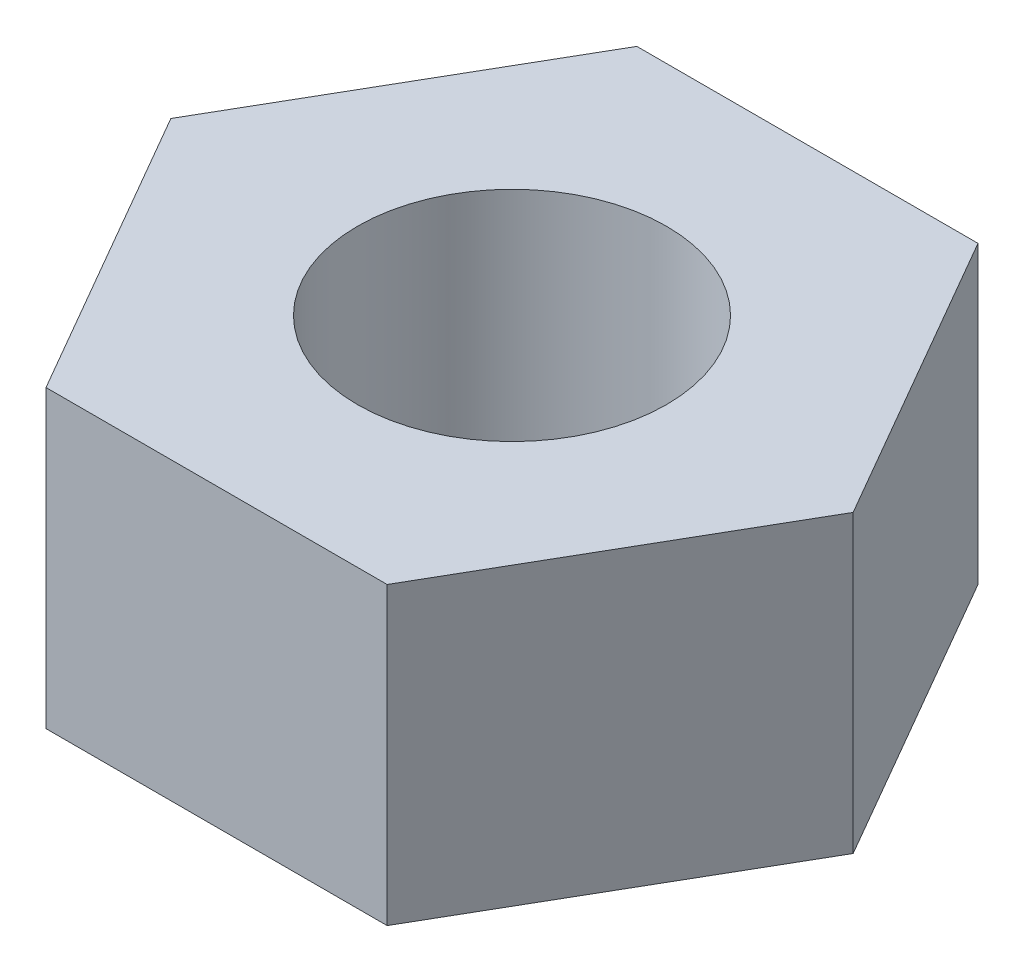
SolidWorks part; units mm, degrees
ref_plane "Front Plane" through (0, 0, 0) normal (0, 0, 1) x (1, 0, 0)
ref_plane "Top Plane" through (0, 0, 0) normal (0, 1, 0) x (1, 0, 0)
ref_plane "Right Plane" through (0, 0, 0) normal (1, 0, 0) x (0, 0, -1)
sketch "Sketch1" plane through (0, 0, 0) normal (0, 1, 0) x (1, 0, 0)
  line L0 (0, 0) -> (0, 6.5) construction
  line L1 (0, 0) -> (4.9464, 8.5675) construction
  line L3 (3.7528, 6.5) -> (-3.7528, 6.5)
  line L4 (-3.7528, 6.5) -> (-7.5056, 0)
  line L5 (-7.5056, 0) -> (-3.7528, -6.5)
  line L6 (-3.7528, -6.5) -> (3.7528, -6.5)
  line L7 (3.7528, -6.5) -> (7.5056, 0)
  line L8 (7.5056, 0) -> (3.7528, 6.5)
  circle A0 centre (0, 0) radius 6.5 construction
extrude "Boss-Extrude1" add sketch "Sketch1" along normal blind 6.5
hole_wizard "Tap Drill for M8x1.25 Tap1" positions "Sketch7" profile "Sketch8" hole size "M8x1.25" standard "BSI" end condition through all
sketch "Sketch7" plane through (0, 6.5, 0) normal (0, 1, 0) x (1, 0, 0)
  point P0 (0, 0)
sketch "Sketch8" plane through (0, 6.5, 0) normal (1, 0, 0) x (0, 0, 1)
  line L0 (0, 0) -> (0, 6.5)
  line L1 (0, 6.5) -> (3.4, 6.5)
  line L2 (3.4, 6.5) -> (3.4, 0)
  line L5 (3.4, 0) -> (0, 0)
  line L11 (0, -6.35) -> (0, 107.95) construction
  dimension "Thru Hole Dia." = 6.8
  dimension "Thru Hole Depth" = 6.5
